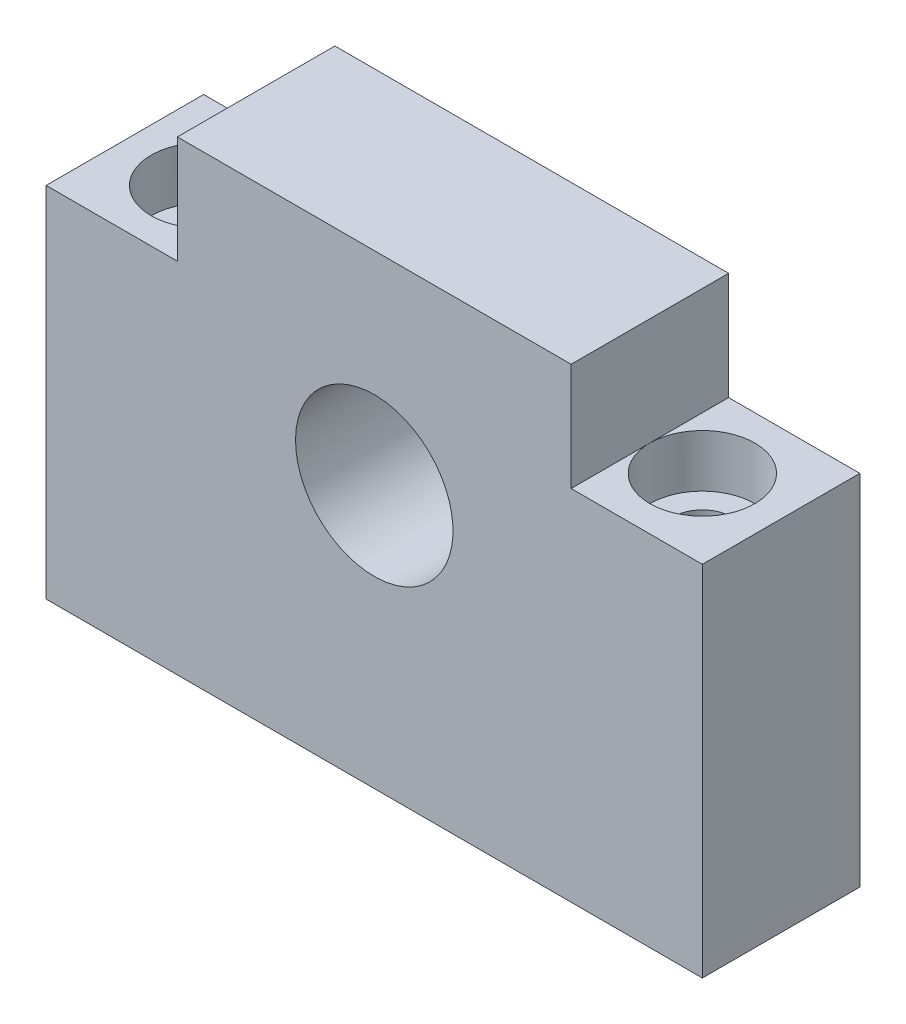
SolidWorks part; units mm, degrees
material "6061 합금"
ref_plane "정면" through (0, 0, 0) normal (0, 0, 1) x (1, 0, 0)
ref_plane "윗면" through (0, 0, 0) normal (0, 1, 0) x (1, 0, 0)
ref_plane "우측면" through (0, 0, 0) normal (1, 0, 0) x (0, 0, -1)
sketch "스케치1" plane through (0, 0, 0) normal (0, 0, 1) x (1, 0, 0)
  line L1 (0, 0) -> (50, 0)
  line L2 (0, 0) -> (0, 27.3)
  line L3 (0, 27.3) -> (50, 27.3)
  line L4 (50, 0) -> (50, 27.3)
  dimension "D1" = 50
  dimension "D2" = 27.3
extrude "보스-돌출1" add sketch "스케치1" along normal blind 12
sketch "스케치2" plane through (0, 0, 12) normal (0, 0, 1) x (1, 0, 0)
  line L0 (25, 27.3) -> (25, 35.5) construction
  line L1 (10, 5.5) -> (40, 5.5)
  line L2 (10, 5.5) -> (10, 35.5)
  line L3 (10, 35.5) -> (40, 35.5)
  line L4 (40, 5.5) -> (40, 35.5)
  line L5 (50, 27.3) -> (0, 27.3) construction
  line L7 (0, 0) -> (50, 0) construction
  dimension "D1" = 30
  dimension "D2" = 30
  dimension "D3" = 5.5
extrude "보스-돌출2" add sketch "스케치2" against normal blind 12
sketch "스케치3" plane through (0, 0, 0) normal (0, 0, -1) x (-1, 0, 0)
  line L0 (0, 0) -> (-50, 0) construction
  circle A0 centre (-25, 20) radius 6
  dimension "D2" = 12
  dimension "D1" = 20
extrude "컷-돌출1" cut sketch "스케치3" against normal through all
hole_wizard "M4 소켓 머리 캡 나사용 카운터보어3" positions "스케치6" profile "스케치5" counterbore size "M4" standard "KS" end condition through all
sketch "스케치6" plane through (0, 27.3, 0) normal (0, 1, 0) x (1, 0, 0)
  line L0 (44, -6) -> (6, -6) construction
  line L1 (6, -6) -> (0, -6) construction
  line L2 (0, -12) -> (0, 0) construction
  line L5 (44, -6) -> (50, -6) construction
  line L6 (50, -12) -> (50, 0) construction
  point P1 (44, -6)
  point P2 (6, -6)
  dimension "D1" = 38
sketch "스케치5" plane through (44, 27.3, 6) normal (1, 0, 0) x (0, 0, 1)
  line L0 (0, 0) -> (0, 27.3)
  line L1 (0, 27.3) -> (2.25, 27.3)
  line L3 (2.25, 27.3) -> (2.25, 4)
  line L4 (2.25, 4) -> (4, 4)
  line L5 (4, 4) -> (4, 0)
  line L7 (4, 0) -> (0, 0)
  line L11 (0, -6.35) -> (0, 107.95) construction
  dimension "관통 구멍 지름" = 4.5
  dimension "관통 구멍 깊이" = 27.3
  dimension "카운터보어 지름" = 8
  dimension "카운터보어 깊이" = 4
